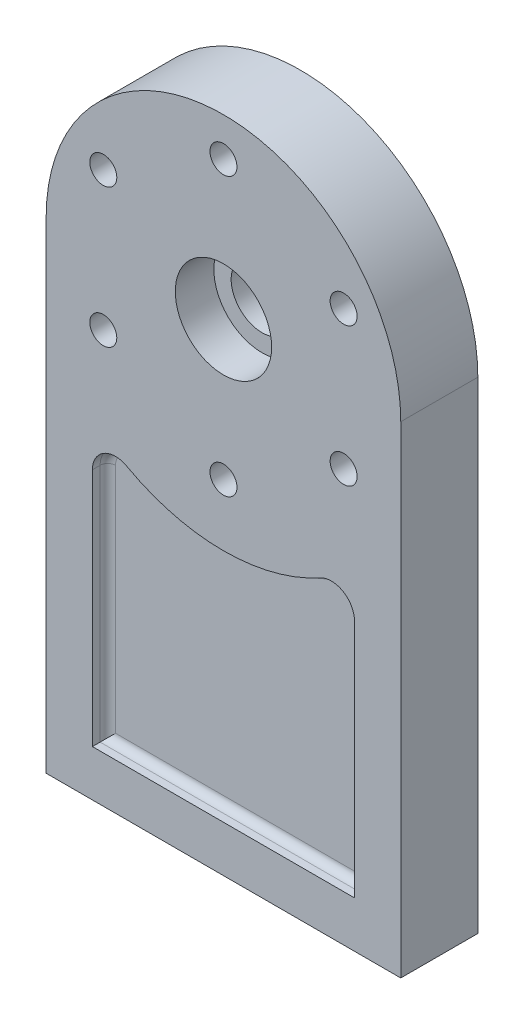
SolidWorks part; units mm, degrees
ref_plane "Front Plane" through (0, 0, 0) normal (0, 0, 1) x (1, 0, 0)
ref_plane "Top Plane" through (0, 0, 0) normal (0, 1, 0) x (1, 0, 0)
ref_plane "Right Plane" through (0, 0, 0) normal (1, 0, 0) x (0, 0, -1)
sketch "Sketch1" plane through (0, 0, 0) normal (0, 0, 1) x (1, 0, 0)
  line L0 (46, 125) -> (46, 0)
  line L1 (46, 0) -> (-46, 0)
  line L2 (-46, 0) -> (-46, 125)
  arc A0 (46, 125) -> (-46, 125) centre (0, 125) ccw
  circle A1 centre (0, 125) radius 8
  dimension "D1" = 125
  dimension "D2" = 92
  dimension "D3" = 16
extrude "Boss-Extrude1" add sketch "Sketch1" along normal mid plane 20
sketch "Sketch3" plane through (0, 0, 10) normal (0, 0, 1) x (1, 0, 0)
  circle A0 centre (0, 125) radius 12.5
  dimension "D1" = 25
extrude "Cut-Extrude1" cut sketch "Sketch3" against normal blind 10
sketch "Sketch4" plane through (0, 0, 10) normal (0, 0, 1) x (1, 0, 0)
  circle A0 centre (0, 161) radius 3.5
  circle A1 centre (0, 125) radius 36 construction
  dimension "D1" = 72
  dimension "D2" = 7
extrude "Cut-Extrude2" cut sketch "Sketch4" against normal through all
hole_wizard "Tap Drill for M10x1.25 Tap1" positions "Sketch6" profile "Sketch7" hole size "M10x1.25" standard "ISO"
sketch "Sketch6" plane through (0, 0, 0) normal (0, -1, 0) x (-1, 0, 0)
  line L0 (46, -10) -> (-46, -10) construction
  line L1 (-46, -10) -> (-46, 10) construction
  point P0 (-30, 0)
  point P2 (30, 0)
  dimension "D1" = 10
  dimension "D2" = 16
  dimension "D3" = 60
sketch "Sketch7" plane through (30, 0, 0) normal (1, 0, 0) x (0, 0, -1)
  line L0 (0, 0) -> (0, 26.6438)
  line L1 (0, 26.6438) -> (4.4, 24)
  line L2 (4.4, 24) -> (4.4, 0.025)
  line L3 (4.4, 0.025) -> (4.425, 0)
  line L5 (4.425, 0) -> (0, 0)
  line L6 (-4.4, 0.025) -> (-4.425, 0) construction
  line L10 (0, 26.6438) -> (-4.4, 24) construction
  line L11 (0, -6.35) -> (0, 107.95) construction
  dimension "Hole Dia." = 8.8
  dimension "Hole Depth" = 24
  dimension "Near C'Sink Dia." = 8.85
  dimension "Near C'Sink Angle" = 90
  dimension "Drill Angle" = 118
sketch "Sketch8" plane through (0, 0, 10) normal (0, 0, 1) x (1, 0, 0)
  line L9 (-34, 125) -> (-34, 12)
  line L10 (-34, 12) -> (34, 12)
  line L11 (34, 12) -> (34, 125)
  line L12 (-34, 74.2063) -> (-34, 12)
  line L13 (-34, 12) -> (34, 12)
  line L14 (34, 12) -> (34, 74.2063)
  arc A0 (-25.1034, 79.4608) -> (25.1034, 79.4608) centre (0, 125) ccw
  arc A1 (25.1034, 79.4608) -> (34, 74.2063) centre (28, 74.2063) cw
  arc A2 (-25.1034, 79.4608) -> (-34, 74.2063) centre (-28, 74.2063) ccw
  dimension "D1" = 104
  dimension "D3" = 6
  dimension "D2" = 12
extrude "Cut-Extrude4" cut sketch "Sketch8" against normal blind 4
fillet "Fillet1" radius 2 6 edges at (34, 43.1031, 6) (0, 12, 6) (-34, 43.1031, 6) (-31.0513, 79.3725, 6) (0, 73, 6) (31.0513, 79.3725, 6)
mirror "Mirror1" about plane through (0, 0, 0) normal (0, 0, 1) of "Cut-Extrude4", "Fillet1"
sketch "Sketch9" plane through (0, 0, -10) normal (0, 0, -1) x (-1, 0, 0)
  circle A0 centre (0, 161) radius 6
  dimension "D1" = 12
extrude "Cut-Extrude5" cut sketch "Sketch9" against normal blind 6
pattern_circular "CirPattern1" count 6 over 360 about axis through (0, 125, 0) along (0, 0, 1) of "Cut-Extrude5", "Cut-Extrude2"
